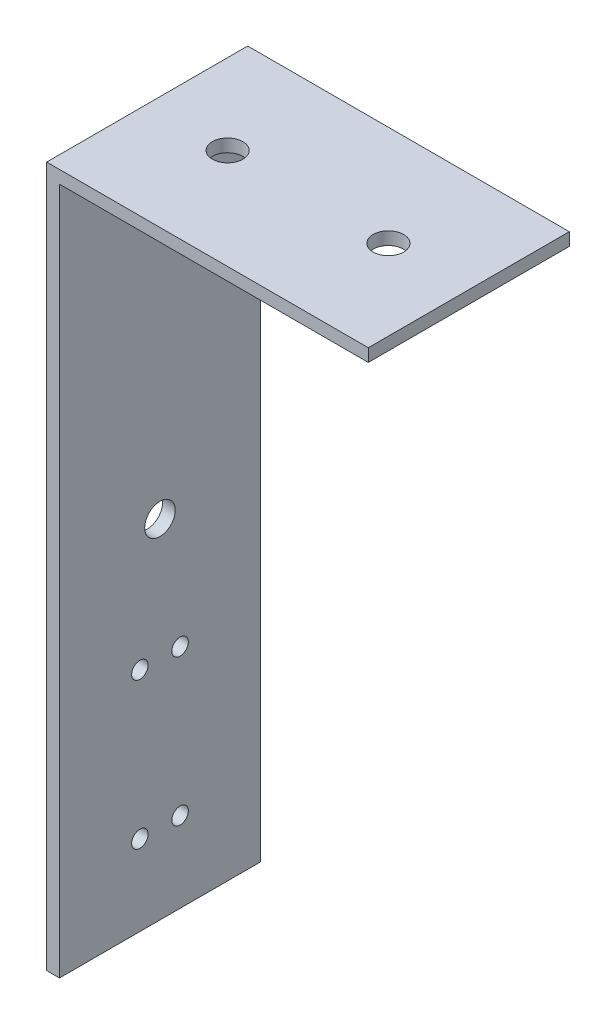
SolidWorks part; units mm, degrees
ref_plane "Front Plane" through (0, 0, 0) normal (0, 0, 1) x (1, 0, 0)
ref_plane "Top Plane" through (0, 0, 0) normal (0, 1, 0) x (1, 0, 0)
ref_plane "Right Plane" through (0, 0, 0) normal (1, 0, 0) x (0, 0, -1)
sketch "Sketch2" plane through (0, 0, 0) normal (0, 0, 1) x (1, 0, 0)
  line L0 (0, 0) -> (0, 87.1)
  line L1 (0, 87.1) -> (40, 87.1)
  line L2 (1.5875, 0) -> (1.5875, 85.5125)
  line L3 (1.5875, 85.5125) -> (40, 85.5125)
  line L4 (40, 87.1) -> (40, 85.5125)
  line L5 (0, 0) -> (1.5875, 0)
  dimension "D1" = 40
  dimension "D2" = 87.1
  dimension "D3" = 1.5875
extrude "Boss-Extrude1" add sketch "Sketch2" along normal blind 25
hole_wizard "#6 Clearance Hole1" positions "Sketch4" profile "Sketch3" hole size "#6" standard "ANSI Inch" end condition through all
sketch "Sketch4" plane through (0, 87.1, 0) normal (0, 1, 0) x (1, 0, 0)
  line L0 (40, 0) -> (0, 0) construction
  line L1 (0, -25) -> (0, 0) construction
  point P0 (10, -12.5)
  point P2 (30, -12.5)
  dimension "D1" = 12.5
  dimension "D2" = 10
  dimension "D3" = 20
sketch "Sketch3" plane through (10, 87.1, 12.5) normal (1, 0, 0) x (0, 0, 1)
  line L0 (0, 0) -> (0, 87.1)
  line L1 (0, 87.1) -> (1.8986, 87.1)
  line L2 (1.8986, 87.1) -> (1.8986, 0)
  line L5 (1.8986, 0) -> (0, 0)
  line L11 (0, -6.35) -> (0, 107.95) construction
  dimension "Thru Hole Dia." = 3.7973
  dimension "Thru Hole Depth" = 87.1
hole_wizard "#1 Clearance Hole2" positions "Sketch8" profile "Sketch7" hole size "#1" standard "ANSI Inch" end condition through all
sketch "Sketch8" plane through (0, 0, 0) normal (-1, 0, 0) x (0, 0, 1)
  line L0 (25, 0) -> (0, 0) construction
  line L1 (25, 87.1) -> (25, 0) construction
  line L2 (0, 0) -> (0, 85.5125) construction
  point P0 (15, 10)
  point P2 (15, 28.2)
  point P10 (10, 10)
  point P12 (10, 28.2)
  dimension "D1" = 10
  dimension "D2" = 10
  dimension "D3" = 18.2
  dimension "D4" = 10
sketch "Sketch7" plane through (0, 10, 15) normal (0, 1, 0) x (0, 0, 1)
  line L0 (0, 0) -> (0, 40)
  line L1 (0, 40) -> (1.0287, 40)
  line L2 (1.0287, 40) -> (1.0287, 0)
  line L5 (1.0287, 0) -> (0, 0)
  line L11 (0, -6.35) -> (0, 107.95) construction
  dimension "Thru Hole Dia." = 2.0574
  dimension "Thru Hole Depth" = 40
hole_wizard "#6 Clearance Hole2" positions "Sketch10" profile "Sketch9" hole size "#6" standard "ANSI Inch" end condition through all
sketch "Sketch10" plane through (0, 0, 0) normal (-1, 0, 0) x (0, 0, 1)
  line L0 (0, 87.1) -> (0, 0) construction
  circle A0 centre (15, 28.2) radius 1.0287 construction
  point P0 (12.5, 43.2)
  dimension "D1" = 15
  dimension "D2" = 12.5
sketch "Sketch9" plane through (0, 43.2, 12.5) normal (0, 1, 0) x (0, 0, 1)
  line L0 (0, 0) -> (0, 40)
  line L1 (0, 40) -> (1.8986, 40)
  line L2 (1.8986, 40) -> (1.8986, 0)
  line L5 (1.8986, 0) -> (0, 0)
  line L11 (0, -6.35) -> (0, 107.95) construction
  dimension "Thru Hole Dia." = 3.7973
  dimension "Thru Hole Depth" = 40
